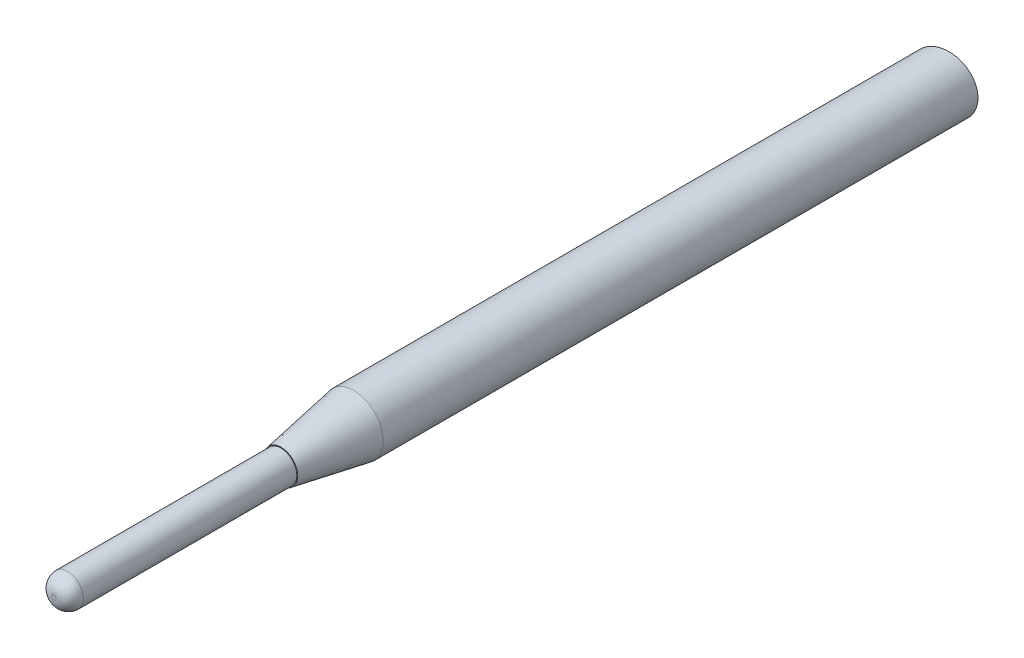
SolidWorks part; units mm, degrees
ref_plane "Plan de face" through (0, 0, 0) normal (0, 0, 1) x (1, 0, 0)
ref_plane "Plan de dessus" through (0, 0, 0) normal (0, 1, 0) x (1, 0, 0)
ref_plane "Plan de droite" through (0, 0, 0) normal (1, 0, 0) x (0, 0, -1)
sketch "Esquisse1" plane through (0, 0, 0) normal (0, 0, 1) x (1, 0, 0)
  circle A0 centre (0, 0) radius 6.5
  dimension "D1" = 13
extrude "Boss.-Extru.1" add sketch "Esquisse1" along normal blind 147
sketch "Esquisse2" plane through (0, 0, 147) normal (0, 0, 1) x (1, 0, 0)
  circle A0 centre (0, 0) radius 3.5
  dimension "D1" = 7
extrude "Boss.-Extru.2" add sketch "Esquisse2" along normal blind 50
fillet "Congé1" radius 3 1 edges at (3.5, 0, 197)
chamfer "Chanfrein1" distance 16 angle 10 1 edges at (6.5, 0, 147)
sketch "Esquisse3" plane through (0, 0, 0) normal (0, 1, 0) x (1, 0, 0)
  line L0 (6.5, 0) -> (-6.5, -1.827)
  line L1 (-6.5, 0) -> (-6.5, -131) construction
  line L2 (-6.5, -1.827) -> (-6.5, 0)
  line L3 (-6.5, 0) -> (6.5, 0)
  dimension "D1" = 8
extrude "Enlèv. mat.-Extru.1" cut sketch "Esquisse3" against normal through all both and the other way through all
sketch "Esquisse4" plane through (0.1259, 0, 0.8958) normal (-0.1392, 0, -0.9903) x (-0.9903, 0, 0.1392)
  line L0 (-1.6076, 1.1898) -> (-1.6076, -1.1898)
  arc A0 (-1.6076, -1.1898) -> (-1.6076, 1.1898) centre (0, 0) ccw
  dimension "D1" = 2
extrude "Enlèv. mat.-Extru.2" cut sketch "Esquisse4" against normal blind 5
